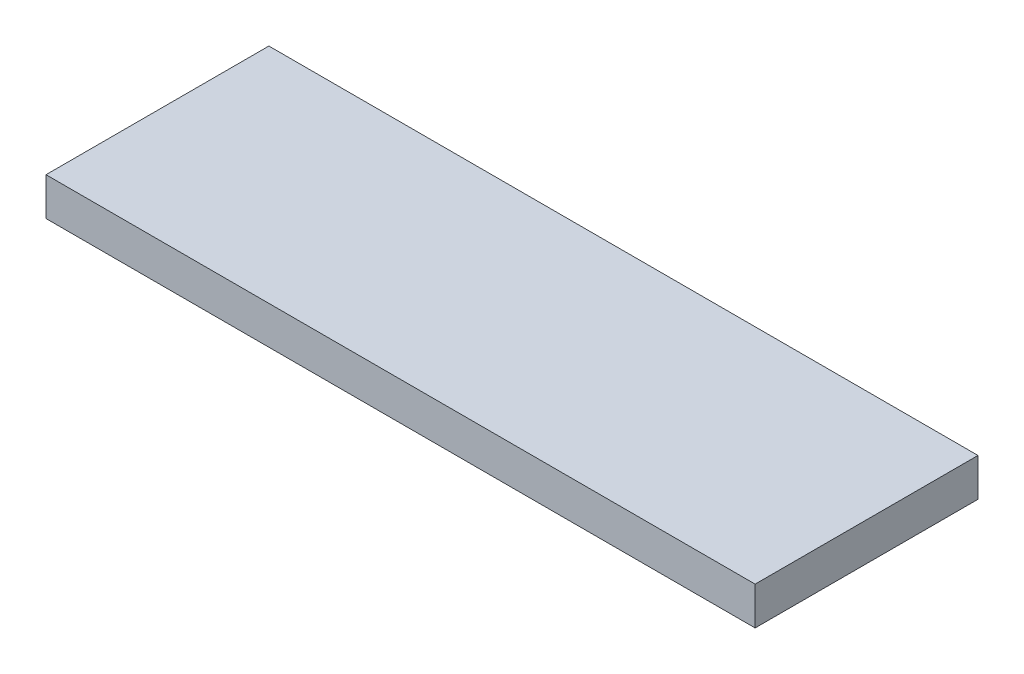
SolidWorks part; units mm, degrees
ref_plane "Front Plane" through (0, 0, 0) normal (0, 0, 1) x (1, 0, 0)
ref_plane "Top Plane" through (0, 0, 0) normal (0, 1, 0) x (1, 0, 0)
ref_plane "Right Plane" through (0, 0, 0) normal (1, 0, 0) x (0, 0, -1)
sketch "Sketch1" plane through (0, 0, 0) normal (0, 1, 0) x (1, 0, 0)
  line L1 (0, 0) -> (-177.8, 0)
  line L2 (0, 0) -> (0, 55.88)
  line L3 (0, 55.88) -> (-177.8, 55.88)
  line L4 (-177.8, 0) -> (-177.8, 55.88)
  dimension "D1" = 177.8
  dimension "D2" = 55.88
extrude "Boss-Extrude1" add sketch "Sketch1" along normal blind 9.525
